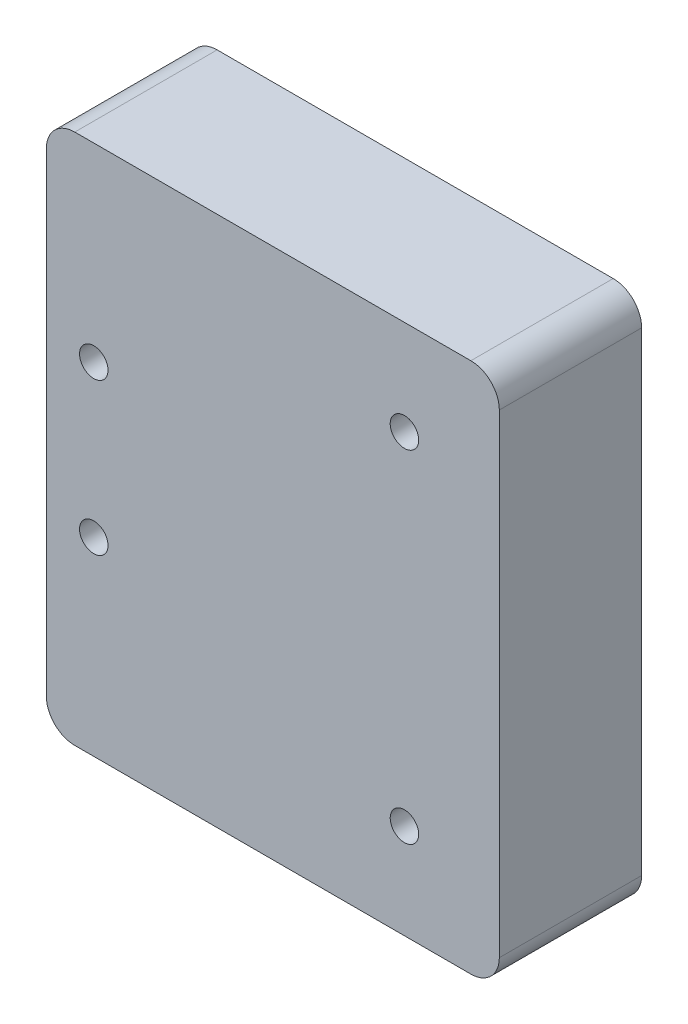
SolidWorks part; units mm, degrees
ref_plane "Plan de face" through (0, 0, 0) normal (0, 0, 1) x (1, 0, 0)
ref_plane "Plan de dessus" through (0, 0, 0) normal (0, 1, 0) x (1, 0, 0)
ref_plane "Plan de droite" through (0, 0, 0) normal (1, 0, 0) x (0, 0, -1)
sketch "Esquisse1" plane through (0, 0, 0) normal (0, 0, 1) x (1, 0, 0)
  line L1 (0, 0) -> (50, 0)
  line L2 (0, 0) -> (0, 60)
  line L3 (0, 60) -> (50, 60)
  line L4 (50, 0) -> (50, 60)
  dimension "D1" = 60
  dimension "D2" = 50
extrude "Boss.-Extru.1" add sketch "Esquisse1" along normal blind 15
sketch "Esquisse2" plane through (0, 0, 0) normal (0, 0, 1) x (1, 0, 0)
  line L0 (0, 60) -> (0, 0) construction
  line L1 (50, 60) -> (0, 60) construction
  circle A0 centre (10, 36.14) radius 4.25
  circle A1 centre (10, 19.84) radius 4.25
  circle A2 centre (24.645, 27.99) radius 5
  dimension "D2" = 10
  dimension "D3" = 8.5
  dimension "D4" = 8.5
  dimension "D5" = 16.3
  dimension "D6" = 16.76
  dimension "D7" = 16.76
  dimension "D8" = 23.86
  dimension "D10" = 10
  dimension "D11" = 10
extrude "Enlèv. mat.-Extru.1" cut sketch "Esquisse2" along normal blind 8
sketch "Esquisse4" plane through (0, 0, 0) normal (0, 0, 1) x (1, 0, 0)
  line L0 (0, 0) -> (50, 0) construction
  line L1 (50, 60) -> (47.7399, 60)
  line L2 (50, 60) -> (50, 0)
  line L3 (50, 0) -> (47.7399, 0)
  line L4 (47.7399, 60) -> (47.7399, 0)
extrude "Enlèv. mat.-Extru.2" cut sketch "Esquisse4" along normal through all
sketch "Esquisse5" plane through (0, 0, 0) normal (1, 0, 0) x (0, 0, -1)
  line L2 (-15, 0) -> (0, 0) construction
  circle A0 centre (-7.78, 8) radius 4
  circle A1 centre (-7.78, 48) radius 4
  dimension "D1" = 8
  dimension "D2" = 8
  dimension "D3" = 40
  dimension "D4" = 8
extrude "Enlèv. mat.-Extru.3" cut sketch "Esquisse5" along normal blind 8
sketch "Esquisse6" plane through (0, 0, 0) normal (0, 0, -1) x (-1, 0, 0)
  line L0 (0, 60) -> (0, 0) construction
  line L1 (-47.7399, 55.984) -> (0, 55.984)
  line L2 (-47.7399, 55.984) -> (-47.7399, 60)
  line L3 (-47.7399, 60) -> (0, 60)
  line L4 (0, 55.984) -> (0, 60)
  line L5 (-47.7399, 60) -> (-47.7399, 0) construction
extrude "Enlèv. mat.-Extru.4" cut sketch "Esquisse6" against normal through all
fillet "Congé1" radius 3 4 edges at (47.7399, 0, 7.5) (47.7399, 55.984, 7.5) (0, 55.984, 7.5) (0, 0, 7.5)
sketch "Esquisse7" plane through (0, 0, 15) normal (0, 0, 1) x (1, 0, 0)
  line L0 (44.7399, 55.984) -> (3, 55.984) construction
  line L1 (47.7399, 52.984) -> (47.7399, 3) construction
  line L2 (3, 0) -> (44.7399, 0) construction
  line L3 (0, 52.984) -> (0, 3) construction
  circle A0 centre (37.7399, 45.984) radius 1.5
  circle A1 centre (37.7399, 10) radius 1.5
  circle A2 centre (5, 20) radius 1.5
  circle A3 centre (5, 35.984) radius 1.5
  dimension "D1" = 3
  dimension "D2" = 3
  dimension "D3" = 3
  dimension "D4" = 3
  dimension "D6" = 10
  dimension "D7" = 10
  dimension "D8" = 10
  dimension "D9" = 5
  dimension "D10" = 5
  dimension "D11" = 20
  dimension "D12" = 20
  dimension "D5" = 10
extrude "Enlèv. mat.-Extru.5" cut sketch "Esquisse7" against normal blind 5
